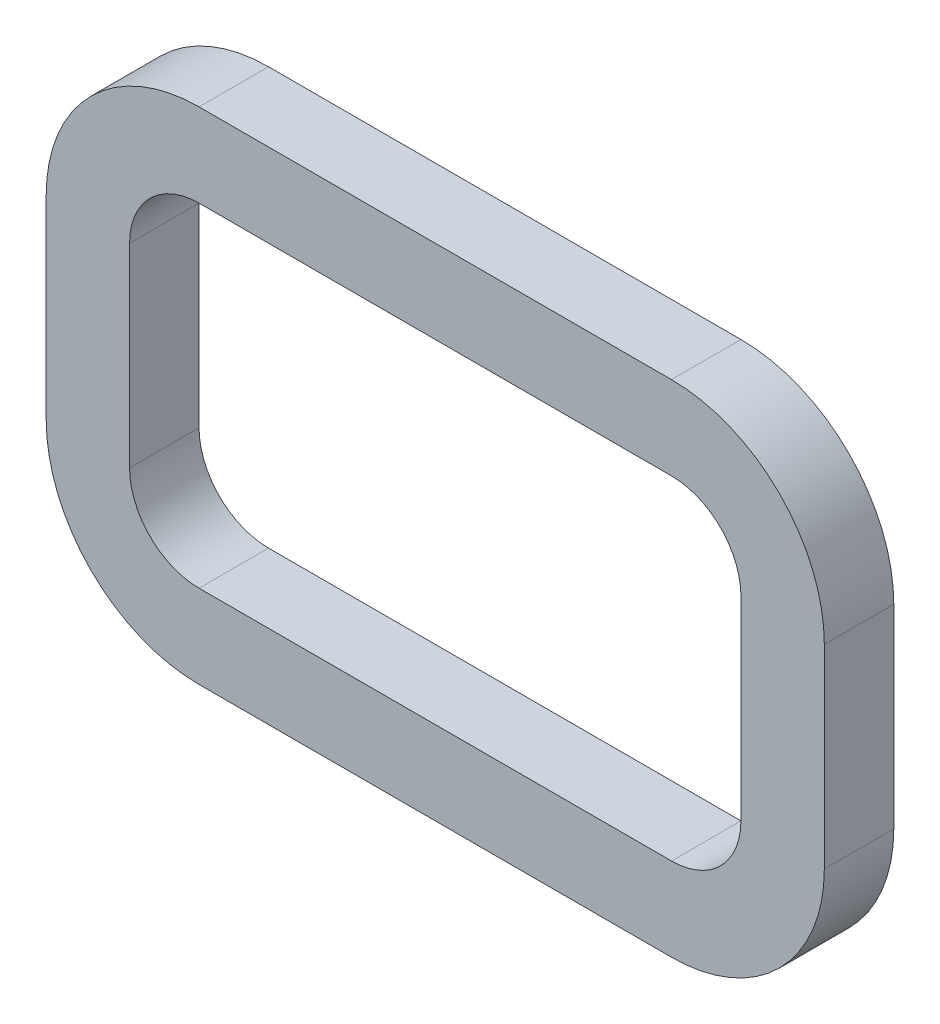
SolidWorks part; units mm, degrees
ref_plane "Front Plane" through (0, 0, 0) normal (0, 0, 1) x (1, 0, 0)
ref_plane "Top Plane" through (0, 0, 0) normal (0, 1, 0) x (1, 0, 0)
ref_plane "Right Plane" through (0, 0, 0) normal (1, 0, 0) x (0, 0, -1)
sketch "Sketch1" plane through (0, 0, 0) normal (0, 0, 1) x (1, 0, 0)
  line L1 (-170, 150) -> (170, 150)
  line L2 (-250, 70) -> (-250, -70)
  line L3 (-170, -150) -> (170, -150)
  line L4 (250, 70) -> (250, -70)
  line L5 (-250, 150) -> (250, -150) construction
  line L6 (-250, -150) -> (250, 150) construction
  arc A0 (170, 150) -> (250, 70) centre (170, 70) cw
  arc A1 (170, -150) -> (250, -70) centre (170, -70) ccw
  arc A2 (-250, -70) -> (-170, -150) centre (-170, -70) ccw
  arc A3 (-170, 150) -> (-250, 70) centre (-170, 70) ccw
  point P0 (0, 0)
  dimension "D3" = 80
  dimension "D1" = 500
  dimension "D2" = 300
extrude "Extrude-Thin1" add sketch "Sketch1" along normal blind 50 thin thin type mid plane wall 60
